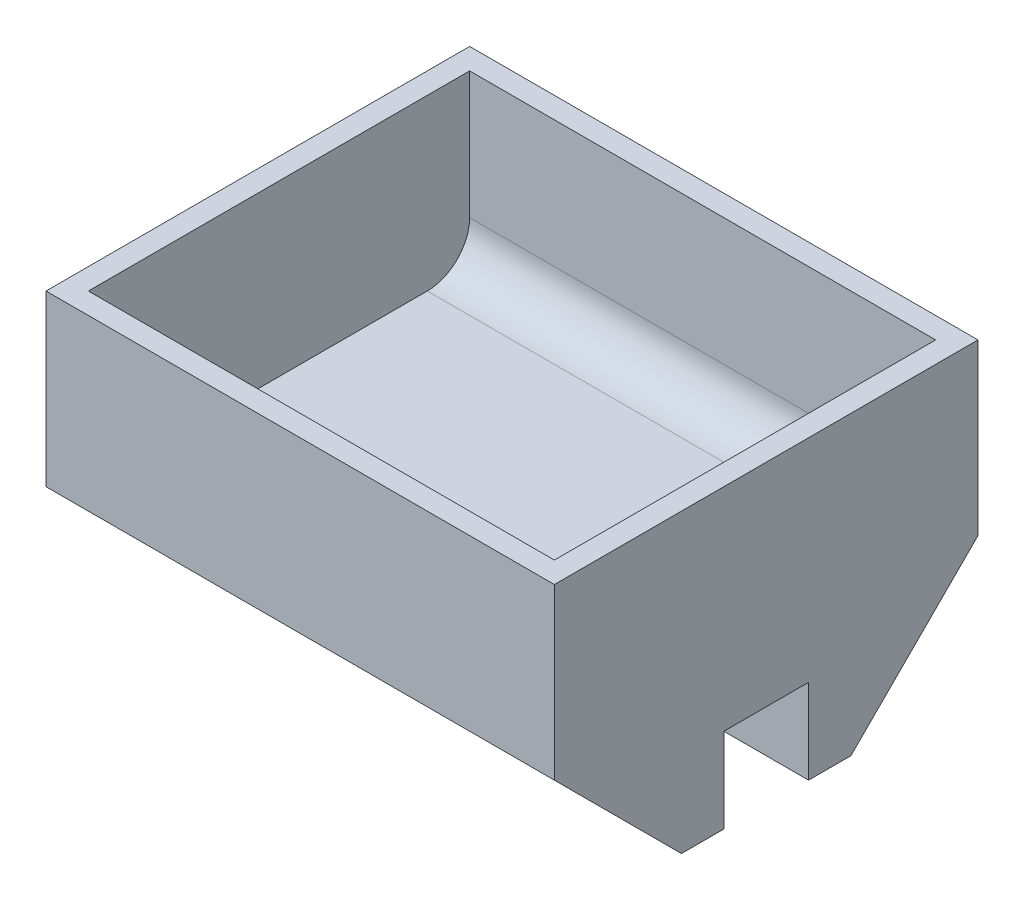
SolidWorks part; units mm, degrees
ref_plane "Front Plane" through (0, 0, 0) normal (0, 0, 1) x (1, 0, 0)
ref_plane "Top Plane" through (0, 0, 0) normal (0, 1, 0) x (1, 0, 0)
ref_plane "Right Plane" through (0, 0, 0) normal (1, 0, 0) x (0, 0, -1)
sketch "Sketch1" plane through (0, 0, 0) normal (0, 0, 1) x (1, 0, 0)
  line L1 (-76.2, 19.05) -> (76.2, 19.05)
  line L2 (-76.2, 19.05) -> (-76.2, -19.05)
  line L3 (-76.2, -19.05) -> (76.2, -19.05)
  line L4 (76.2, 19.05) -> (76.2, -19.05)
  line L5 (-76.2, 19.05) -> (76.2, -19.05) construction
  line L6 (-76.2, -19.05) -> (76.2, 19.05) construction
  point P1 (0, 0)
  dimension "D1" = 38.1
  dimension "D2" = 152.4
extrude "Boss-Extrude1" add sketch "Sketch1" along normal blind 50.8
sketch "Sketch2" plane through (-76.2, 0, 0) normal (-1, 0, 0) x (0, 0, 1)
  line L0 (50.8, -19.05) -> (0, -19.05) construction
  line L1 (12.7, -19.05) -> (38.1, -19.05)
  line L2 (12.7, -19.05) -> (12.7, 6.35)
  line L3 (12.7, 6.35) -> (38.1, 6.35)
  line L4 (38.1, -19.05) -> (38.1, 6.35)
  line L5 (50.8, 19.05) -> (0, 19.05) construction
  point P8 (25.4, 19.05)
  point P9 (25.4, -19.05)
  dimension "D1" = 25.4
extrude "Cut-Extrude1" cut sketch "Sketch2" against normal up to surface (152.4 mm away) up to face at (76.2, 0, 25.4)
sketch "Sketch5" plane through (76.2, 0, 0) normal (1, 0, 0) x (0, 0, -1)
  line L0 (0, -19.05) -> (38.1, 19.05)
  line L2 (0, 19.05) -> (0, -19.05)
  line L3 (-50.8, 19.05) -> (0, 19.05) construction
  line L6 (-88.9, 19.05) -> (-88.9, 69.85)
  line L8 (-25.4, 19.05) -> (-25.4, -29.2356) construction
  line L10 (38.1, 19.05) -> (38.1, 69.85)
  line L13 (-50.8, 19.05) -> (-50.8, -19.05)
  line L15 (-50.8, -19.05) -> (-88.9, 19.05)
  line L16 (-88.9, 69.85) -> (38.1, 69.85)
  line L17 (-50.8, 19.05) -> (0, 19.05)
  point P17 (-78.74, 19.05)
  point P23 (27.94, 19.05)
  dimension "D1" = 38.1
  dimension "D2" = 50.8
extrude "Boss-Extrude2" add sketch "Sketch5" against normal up to surface (152.4 mm away) up to face at (-76.2, -3.175, 25.4)
sketch "Sketch6" plane through (0, 0, 38.1) normal (0, 0, -1) x (-1, 0, 0)
  line L0 (-83.5131, -6.35) -> (84.5521, -6.35) construction
  line L1 (76.2, -19.05) -> (-76.2, -19.05) construction
  circle A1 centre (0, -6.35) radius 6.35
  circle A2 centre (-50.8, -6.35) radius 6.35
  circle A3 centre (50.8, -6.35) radius 6.35
  dimension "D2" = 12.7
  dimension "D3" = 50.8
  dimension "D4" = 50.8
  dimension "D1" = 12.7
extrude "Cut-Extrude3" cut sketch "Sketch6" against normal through all both and the other way through all
sketch "Sketch10" plane through (0, 0, 12.7) normal (0, 0, 1) x (1, 0, 0)
  circle A0 centre (-50.8, -6.35) radius 3.429
  circle A1 centre (0, -6.35) radius 3.429
  circle A2 centre (50.8, -6.35) radius 3.429
  circle A3 centre (-50.8, -6.35) radius 6.35
  circle A4 centre (0, -6.35) radius 6.35
  circle A5 centre (50.8, -6.35) radius 6.35
  dimension "D1" = 6.858
  dimension "D2" = 12.7
extrude "Boss-Extrude3" add sketch "Sketch10" against normal blind 10.16
ref_plane "Plane1" through (0, 0, 25.4) normal (0, 0, 1) x (1, 0, 0)
ref_plane "Plane2" through (0, 0, 0) normal (1, 0, 0) x (0, 0, -1)
sketch "Sketch11" plane through (0, 0, 0) normal (1, 0, 0) x (0, 0, -1)
  line L0 (-82.55, 69.85) -> (-82.55, 31.75)
  line L1 (38.1, 69.85) -> (-88.9, 69.85) construction
  line L2 (-69.85, 19.05) -> (19.05, 19.05)
  line L3 (31.75, 31.75) -> (31.75, 69.85)
  line L4 (-82.55, 69.85) -> (31.75, 69.85)
  arc A0 (-82.55, 31.75) -> (-69.85, 19.05) centre (-69.85, 31.75) ccw
  arc A1 (19.05, 19.05) -> (31.75, 31.75) centre (19.05, 31.75) ccw
  dimension "D1" = 12.7
  dimension "D2" = 6.35
  dimension "D3" = 6.35
extrude "Cut-Extrude4" cut sketch "Sketch11" against normal mid plane 139.7
mirror "Mirror1" about plane through (0, 0, 25.4) normal (0, 0, 1) of "Boss-Extrude3"
